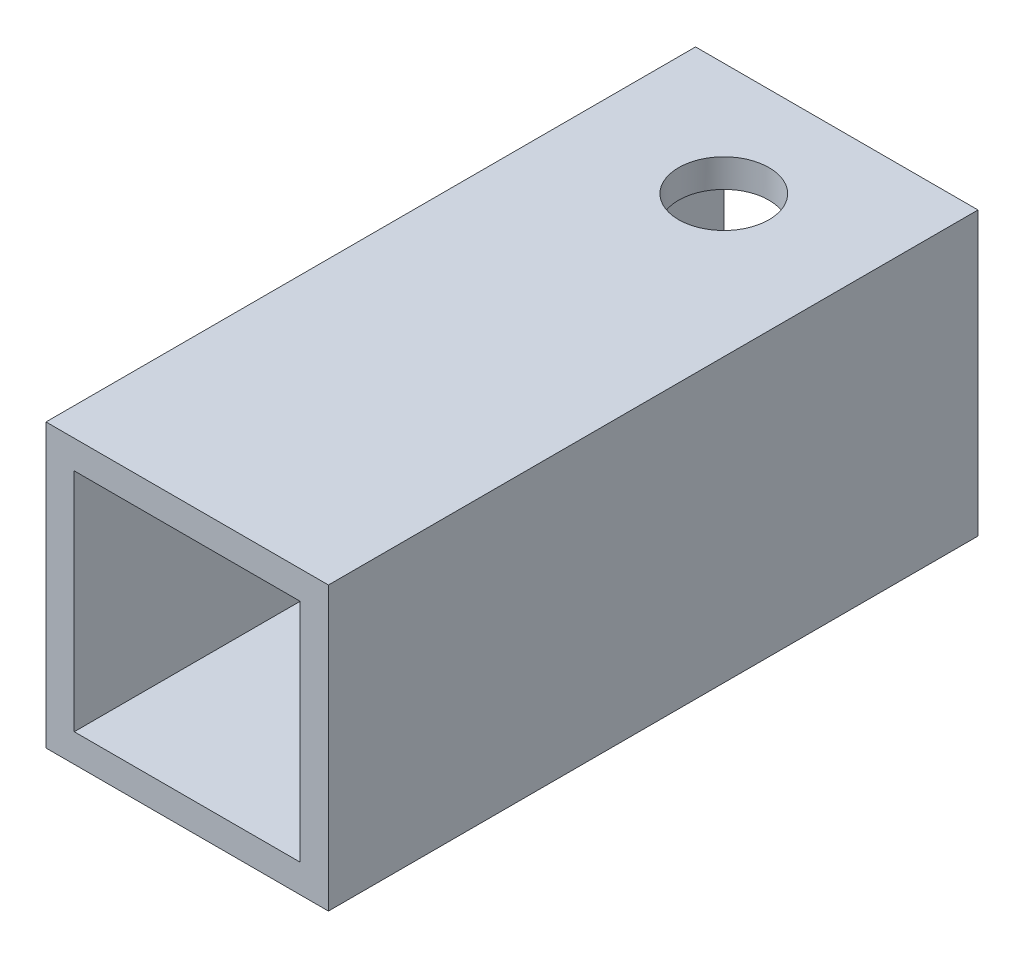
SolidWorks part; units mm, degrees
material "6061 合金"
ref_plane "正面" through (0, 0, 0) normal (0, 0, 1) x (1, 0, 0)
ref_plane "平面" through (0, 0, 0) normal (0, 1, 0) x (1, 0, 0)
ref_plane "右側面" through (0, 0, 0) normal (1, 0, 0) x (0, 0, -1)
sketch "断面 スケッチ" plane through (0, 0, 0) normal (0, 0, 1) x (1, 0, 0)
  line L1 (-5, -5) -> (5, -5)
  line L2 (-5, -5) -> (-5, 5)
  line L3 (-5, 5) -> (5, 5)
  line L4 (5, -5) -> (5, 5)
  line L5 (-5, -5) -> (5, 5) construction
  line L6 (-5, 5) -> (5, -5) construction
  point P0 (0, 0)
  dimension "D1" = 10
extrude "フレーム全長" add sketch "断面 スケッチ" along normal blind 23 thin thin type one direction reverse wall 1
sketch "上面穴 スケッチ" plane through (0, 5, 0) normal (0, 1, 0) x (1, 0, 0)
  line L0 (0, 0) -> (0, -23) construction
  line L1 (5, 0) -> (-5, 0) construction
  line L2 (5, -23) -> (-5, -23) construction
  line L3 (-5, -11.5) -> (5, -11.5) construction
  line L4 (-5, -23) -> (-5, 0) construction
  line L5 (5, -23) -> (5, 0) construction
  circle A0 centre (0, -4) radius 1.6
  dimension "D1" = 4
  dimension "D2" = 3.2
sketch "側面穴 スケッチ" plane through (5, 0, 0) normal (1, 0, 0) x (0, 0, -1)
  line L0 (0, 0) -> (-23, 0) construction
  line L1 (0, -5) -> (0, 5) construction
  line L2 (-23, -5) -> (-23, 5) construction
  line L3 (-11.5, 5) -> (-11.5, -5) construction
  line L4 (-23, 5) -> (0, 5) construction
  line L5 (-23, -5) -> (0, -5) construction
  circle A0 centre (-15, 0) radius 1.6
  dimension "D1" = 15
  dimension "D2" = 3.2
extrude "上面穴貫通" cut sketch "上面穴 スケッチ" against normal through all
extrude "側面穴貫通" [suppressed] cut sketch "側面穴 スケッチ" against normal through all
fillet "フィレット" [suppressed] radius 5
